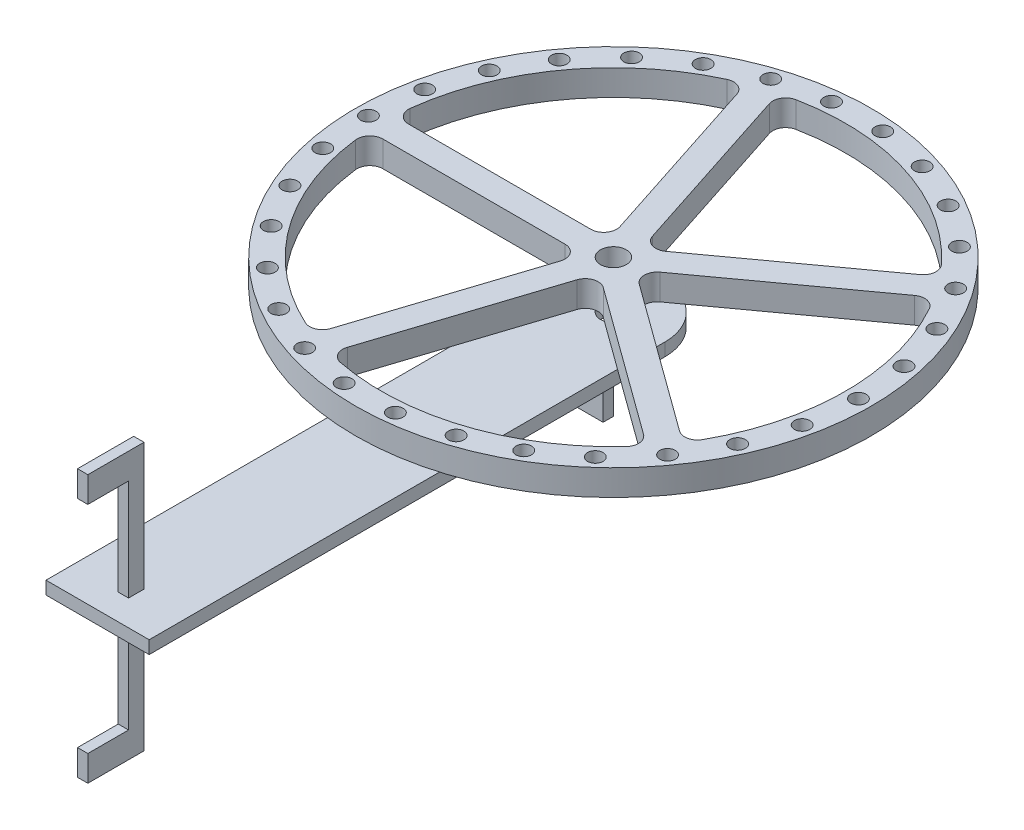
SolidWorks part; units mm, degrees
ref_plane "Front Plane" through (0, 0, 0) normal (0, 0, 1) x (1, 0, 0)
ref_plane "Top Plane" through (0, 0, 0) normal (0, 1, 0) x (1, 0, 0)
ref_plane "Right Plane" through (0, 0, 0) normal (1, 0, 0) x (0, 0, -1)
sketch "Sketch1" plane through (0, 0, 0) normal (0, 1, 0) x (1, 0, 0)
  circle A0 centre (0, 0) radius 50
  dimension "D1" = 100
extrude "Boss-Extrude1" add sketch "Sketch1" along normal blind 5
ref_plane "Plane1" through (0, 5, 0) normal (0, 1, 0) x (1, 0, 0)
sketch "Sketch4" plane through (0, 5, 0) normal (0, 1, 0) x (1, 0, 0)
  line L4 (4.0981, 6.0676) -> (32.675, 26.8299)
  line L7 (4.0981, -6.0676) -> (32.675, -26.8299)
  line L8 (0.251, -7.3176) -> (-10.6644, -40.9117)
  line L9 (-4.5043, -5.7725) -> (-15.4197, -39.3667)
  line L10 (-6.8819, 2.5) -> (-42.2049, 2.5)
  line L11 (-4.5043, 5.7725) -> (-15.4197, 39.3667)
  line L12 (0.251, 7.3176) -> (-10.6644, 40.9117)
  line L13 (7.037, -2.0225) -> (35.6139, -22.7849)
  line L15 (7.037, 2.0225) -> (35.6139, 22.7849)
  line L17 (-6.8819, -2.5) -> (-42.2049, -2.5)
  arc A0 (-18.8442, 40.8644) -> (-44.6875, 5.2941) centre (0, 0) ccw
  arc A1 (-44.6875, -5.2941) -> (-18.8442, -40.8644) centre (0, 0) ccw
  arc A2 (-42.2049, -2.5) -> (-44.6875, -5.2941) centre (-42.2049, -5) ccw
  arc A3 (-42.2049, 2.5) -> (-44.6875, 5.2941) centre (-42.2049, 5) cw
  arc A4 (-10.6644, 40.9117) -> (-8.7742, 44.1363) centre (-8.2867, 41.6843) cw
  arc A5 (-15.4197, 39.3667) -> (-18.8442, 40.8644) centre (-17.7973, 38.5941) ccw
  arc A6 (35.6139, 22.7849) -> (39.2647, 21.9836) centre (37.0834, 20.7623) cw
  arc A7 (32.675, 26.8299) -> (33.0411, 30.5497) centre (31.2055, 28.8525) ccw
  arc A8 (32.675, -26.8299) -> (33.0411, -30.5497) centre (31.2055, -28.8525) cw
  arc A9 (35.6139, -22.7849) -> (39.2647, -21.9836) centre (37.0834, -20.7623) ccw
  arc A10 (-15.4197, -39.3667) -> (-18.8442, -40.8644) centre (-17.7973, -38.5941) cw
  arc A11 (-10.6644, -40.9117) -> (-8.7742, -44.1363) centre (-8.2867, -41.6843) ccw
  arc A12 (33.0411, 30.5497) -> (-8.7742, 44.1363) centre (0, 0) ccw
  arc A13 (39.2647, -21.9836) -> (39.2647, 21.9836) centre (0, 0) ccw
  arc A14 (-8.7742, -44.1363) -> (33.0411, -30.5497) centre (0, 0) ccw
  arc A15 (-6.8819, 2.5) -> (-4.5043, 5.7725) centre (-6.8819, 5) ccw
  arc A16 (0.251, 7.3176) -> (4.0981, 6.0676) centre (2.6287, 8.0902) ccw
  arc A17 (7.037, 2.0225) -> (7.037, -2.0225) centre (8.5065, 0) ccw
  arc A18 (4.0981, -6.0676) -> (0.251, -7.3176) centre (2.6287, -8.0902) ccw
  arc A19 (-4.5043, -5.7725) -> (-6.8819, -2.5) centre (-6.8819, -5) ccw
  circle A20 centre (0, 0) radius 2.5
  point P46 (0, 0)
  dimension "D3" = 90
  dimension "D1" = 2.5
  dimension "D4" = 2.5
  dimension "D5" = 5
  dimension "D2" = 5
extrude "Cut-Extrude1" cut sketch "Sketch4" against normal through all
sketch "Sketch5" plane through (0, 5, 0) normal (0, 1, 0) x (1, 0, 0)
  line L0 (0, 0) -> (-80.5058, 0) construction
  circle A0 centre (0, 0) radius 47.5 construction
sketch "Sketch7" plane through (0, 5, 0) normal (0, 1, 0) x (1, 0, 0)
  line L0 (200000, 0) -> (-200080.5058, 0) construction
  circle A0 centre (-47.5, 0) radius 1.5
  circle A1 centre (0, 0) radius 47.5 construction
extrude "Cut-Extrude2" cut sketch "Sketch7" against normal blind 10
pattern_circular "CirPattern1" count 30 over 360 about axis through (0, 0, 0) along (0, 1, 0) of "Cut-Extrude2"
sketch "Sketch8" plane through (0, 0, 0) normal (0, 0, 1) x (1, 0, 0)
  line L0 (0, 0) -> (0, -25.2551) construction
  line L1 (0, -4.2233) -> (-10, -4.2233)
  line L2 (-10, -4.2233) -> (-10, -6.7233)
  line L3 (-10, -6.7233) -> (10, -6.7233)
  line L4 (10, -6.7233) -> (10, -4.2233)
  line L5 (10, -4.2233) -> (0, -4.2233)
  dimension "D1" = 2.5
  dimension "D2" = 10
extrude "Boss-Extrude3" add sketch "Sketch8" along normal blind 100
sketch "Feet" plane through (0, 0, 0) normal (1, 0, 0) x (0, 0, -1)
  line L0 (-95, -4.2233) -> (-95, 15.4334)
  line L2 (-95, 15.4334) -> (-102.8915, 15.4334)
  line L3 (-102.8915, 15.4334) -> (-102.8915, 20.4334)
  line L4 (-102.8915, 20.4334) -> (-92, 20.4334)
  line L5 (-92, 20.4334) -> (-92, -4.2233)
  line L6 (-95, -4.2233) -> (-92, -4.2233)
  line L7 (-100, -6.7233) -> (-100, -4.2233) construction
  point P10 (-92, -4.2233)
  point P12 (0, 0)
  point P13 (0, 0)
  point P14 (0, 0)
  point P15 (0, 0)
  point P16 (0, 0)
  dimension "D1" = 5
  dimension "D2" = 3
  dimension "D3" = 5
sketch "Sketch11" plane through (0, -6.7233, 0) normal (0, -1, 0) x (1, 0, 0)
  circle A0 centre (0, 0) radius 10
  point P3 (0, 0)
extrude "Boss-Extrude5" add sketch "Sketch11" against normal blind 2.5
sketch "Sketch13" plane through (0, -4.2233, 0) normal (0, 1, 0) x (1, 0, 0)
  circle A0 centre (0, 0) radius 2.5
extrude "Cut-Extrude3" cut sketch "Sketch13" against normal blind 2.5
sketch "Sketch14" plane through (0, -6.7233, 0) normal (0, -1, 0) x (1, 0, 0)
  line L0 (0, 5) -> (5, 5)
  line L1 (0, 5) -> (-5, 5)
  line L2 (-5, 5) -> (-5, 7)
  line L3 (-5, 7) -> (5, 7)
  line L4 (5, 7) -> (5, 5)
  circle A0 centre (0, 0) radius 5 construction
  point P5 (0, 0)
  dimension "D1" = 2
extrude "Boss-Extrude6" add sketch "Sketch14" along normal blind 10
extrude "Boss-Extrude9" add sketch "Feet" along normal blind 1 and the other way blind 1
sketch "Sketch16" plane through (0, 0, 100) normal (0, 0, 1) x (1, 0, 0)
  line L0 (0, -13.5504) -> (0, -1.1454) construction
  line L1 (-10, -5.4733) -> (10, -5.4733) construction
  line L2 (-10, -4.2233) -> (-10, -6.7233) construction
  line L3 (10, -6.7233) -> (10, -4.2233) construction
  point P4 (0, -7.3479)
ref_plane "Plane5" through (0, -5.4733, 0) normal (0, 1, 0) x (1, 0, 0)
mirror "Mirror1" about plane through (0, -5.4733, 0) normal (0, 1, 0) of "Boss-Extrude9"
